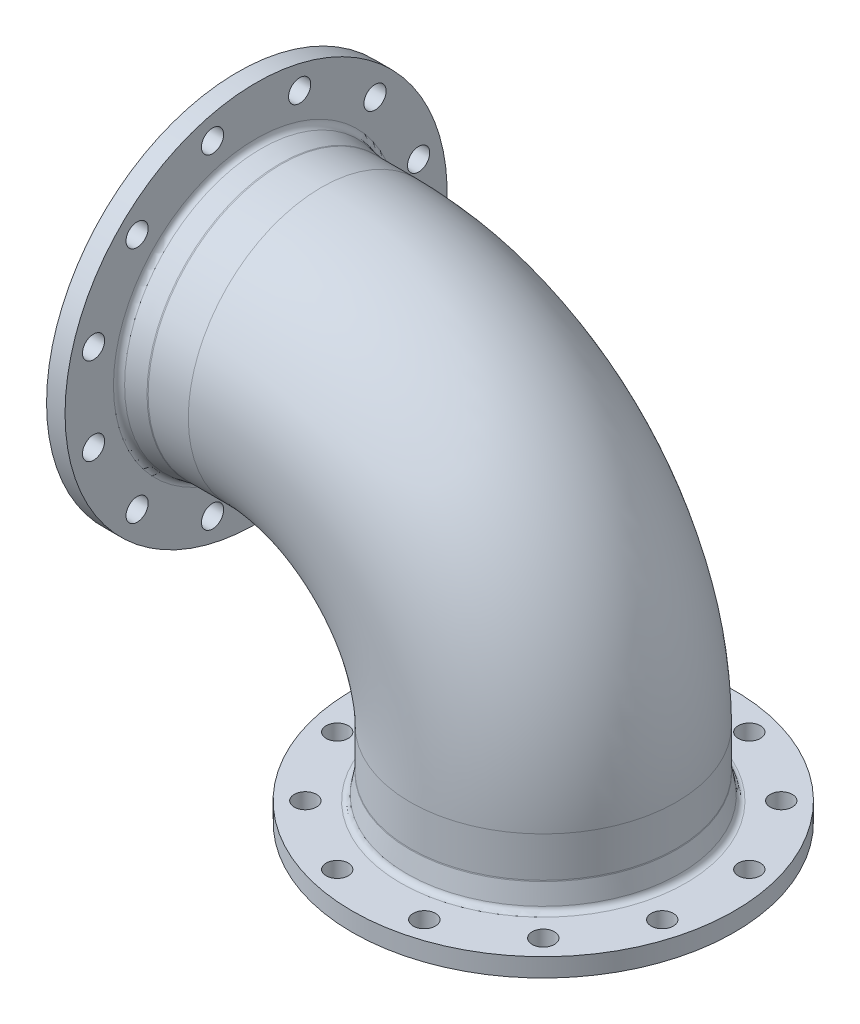
SolidWorks part; units mm, degrees
ref_plane "Front" through (0, 0, 0) normal (0, 0, 1) x (1, 0, 0)
ref_plane "Top" through (0, 0, 0) normal (0, 1, 0) x (1, 0, 0)
ref_plane "Right" through (0, 0, 0) normal (1, 0, 0) x (0, 0, -1)
sketch "Чертеж детали" plane through (0, 0, 0) normal (0, 0, 1) x (1, 0, 0)
  line L0 (921.9109, 823.5907) -> (2575.2443, 823.5907) construction
sketch "Эскиз1" plane through (0, 0, 0) normal (0, 0, 1) x (1, 0, 0)
  line L0 (0, 250) -> (247.7477, 250) construction
  line L1 (0, 350) -> (0, 375)
  line L2 (0, 375) -> (2, 377)
  line L3 (2, 377) -> (2, 405)
  line L4 (2, 405) -> (17, 405)
  line L5 (17, 405) -> (17, 365.722)
  line L6 (21.1318, 360.798) -> (36.5692, 358.076)
  line L7 (37.4374, 358) -> (70, 358)
  line L8 (70, 358) -> (70, 350)
  line L9 (70, 350) -> (0, 350)
  arc A0 (36.5692, 358.076) -> (37.4374, 358) centre (37.4374, 363) ccw
  arc A1 (17, 365.722) -> (21.1318, 360.798) centre (22, 365.722) ccw
  point P11 (114.4557, 373.3587)
  point P13 (17, 360.088)
  point P16 (37, 358)
  point P19 (17, 361.5265)
  dimension "D12" = 5
  dimension "D1" = 250
  dimension "D2" = 200
  dimension "D3" = 250
  dimension "D4" = 45
  dimension "D5" = 10
  dimension "D6" = 8
  dimension "D7" = 70
  dimension "D8" = 310
  dimension "D9" = 2
  dimension "D10" = 17
  dimension "D11" = 20
revolve "Повернуть1" add sketch "Эскиз1" angle 360 about L0
sketch "Эскиз2" plane through (0, 0, 0) normal (0, 0, 1) x (1, 0, 0)
  line L0 (70, 150) -> (70, 350) construction
  line L1 (70, 250) -> (0, 250) construction
  arc A0 (70, 250) -> (250, 70) centre (70, 70) cw
  point P3 (0, 0)
  point P8 (0, 0)
  dimension "D1" = 180
sketch "Эскиз4" plane through (2, 0, 0) normal (1, 0, 0) x (0, 0, -1)
  line L0 (0, 250) -> (0, 442.7535) construction
  circle A0 centre (0, 250) radius 136.5 construction
  circle A1 centre (-35.3288, 381.8489) radius 9
  circle A2 centre (35.3288, 381.8489) radius 9
  circle A3 centre (96.5201, 346.5201) radius 9
  circle A4 centre (131.8489, 285.3288) radius 9
  circle A5 centre (131.8489, 214.6712) radius 9
  circle A6 centre (96.5201, 153.4799) radius 9
  circle A7 centre (35.3288, 118.1511) radius 9
  circle A8 centre (-35.3288, 118.1511) radius 9
  circle A9 centre (-96.5201, 153.4799) radius 9
  circle A10 centre (-131.8489, 214.6712) radius 9
  circle A11 centre (-131.8489, 285.3288) radius 9
  circle A12 centre (-96.5201, 346.5201) radius 9
  point P5 (0, 0)
  point P29 (0, 250)
  point P31 (138.2327, 357.9536)
  point P32 (0, 250)
  dimension "D1" = 12
  dimension "D2" = 273
  dimension "D3" = 18
extrude "Вырез-Вытянуть1" cut sketch "Эскиз4" along normal up to next
sketch "Эскиз3" plane through (70, 0, 0) normal (1, 0, 0) x (0, 0, -1)
  circle A0 centre (0, 250) radius 108 construction
  circle A1 centre (0, 250) radius 100 construction
  circle A2 centre (0, 250) radius 108
  circle A3 centre (0, 250) radius 100
sweep "По траектории1" add profiles "Эскиз3" path "Эскиз2"
ref_plane "Плоскость1" through (0, 0, 0) normal (0.7071, -0.7071, 0) x (-0.7071, -0.7071, 0)
mirror "Зеркальное отражение1" about plane through (0, 0, 0) normal (0.7071, -0.7071, 0) of "Вырез-Вытянуть1", "Повернуть1"
